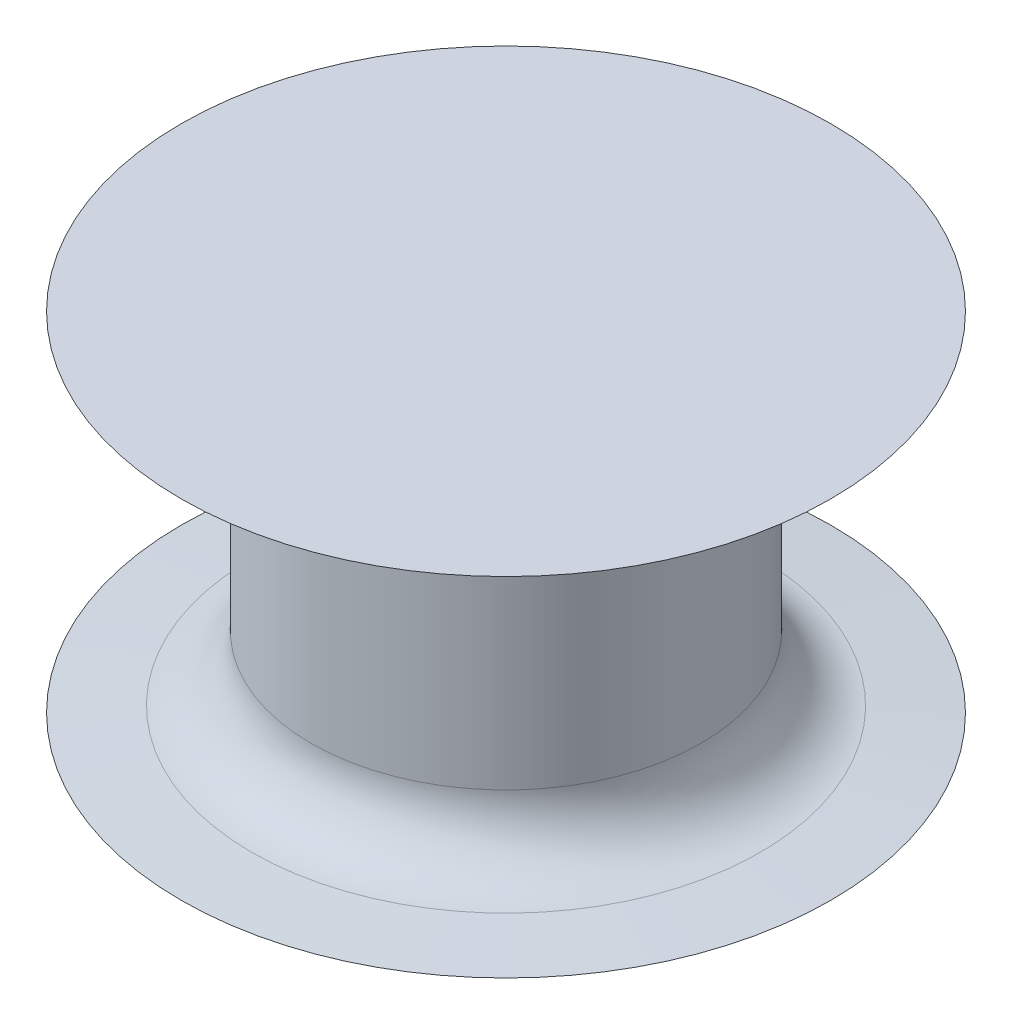
SolidWorks part; units mm, degrees
ref_plane "Front Plane" through (0, 0, 0) normal (0, 0, 1) x (1, 0, 0)
ref_plane "Top Plane" through (0, 0, 0) normal (0, 1, 0) x (1, 0, 0)
ref_plane "Right Plane" through (0, 0, 0) normal (1, 0, 0) x (0, 0, -1)
sketch "Sketch1" plane through (0, 0, 0) normal (0, 1, 0) x (1, 0, 0)
  circle A0 centre (0, 0) radius 1.5
  dimension "D1" = 3
extrude "Boss-Extrude1" add sketch "Sketch1" along normal blind 2.5
sketch "Sketch3" plane through (0, 0, 0) normal (1, 0, 0) x (0, 0, -1)
  line L0 (1.5, 2.5) -> (2.5, 2.5875)
  line L1 (2.5, 2.5875) -> (0, 2.5875)
  line L2 (0, 2.5875) -> (0, 1.5875)
  line L5 (1.5, 2.5) -> (1.5, 1.5875)
  line L6 (1.5, 0) -> (1.5, 2.5) construction
  line L7 (1.5, 1.5875) -> (0, 1.5875)
  dimension "D1" = 95
  dimension "D2" = 2.5
  dimension "D3" = 1
revolve "Revolve1" add sketch "Sketch3" angle 360 about L2
fillet "Fillet1" radius 0.5 1 edges at (0, 2.5, 1.5)
ref_plane "Plane1" through (0, 1.25, 0) normal (0, -1, 0) x (-1, 0, 0)
mirror "Mirror1" about plane through (0, 1.25, 0) normal (0, -1, 0) of "Fillet1", "Revolve1"
